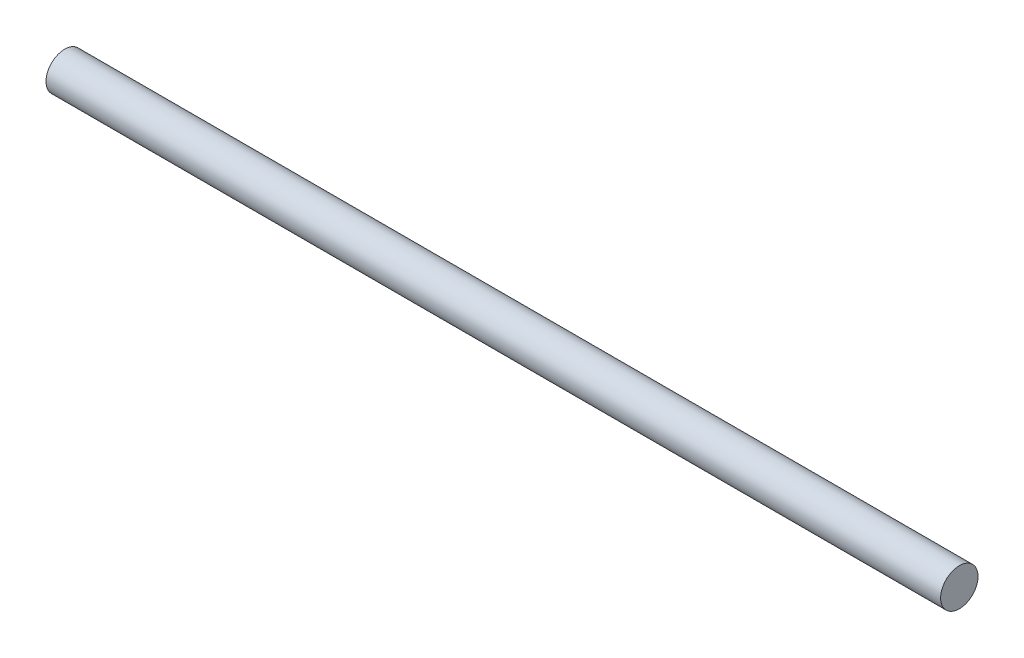
SolidWorks part; units mm, degrees
material "3.0205 (EN-AW 1200)"
ref_plane "Front Plane" through (0, 0, 0) normal (0, 0, 1) x (1, 0, 0)
ref_plane "Top Plane" through (0, 0, 0) normal (0, 1, 0) x (1, 0, 0)
ref_plane "Right Plane" through (0, 0, 0) normal (1, 0, 0) x (0, 0, -1)
sketch "Sketch1" plane through (0, 0, 0) normal (1, 0, 0) x (0, 0, -1)
  circle A0 centre (0, 0) radius 1.27
  dimension "D1" = 2.54
extrude "Boss-Extrude1" add sketch "Sketch1" along normal blind 60.7441
equation "\"Length\" = 2.3915in"
equation "\"Width\" = .1"
equation "\"D1@Boss-Extrude1\"=\"Length\""
equation "\"Force\" = 300"
equation "\"D1@Sketch1\"=\"Width\""
